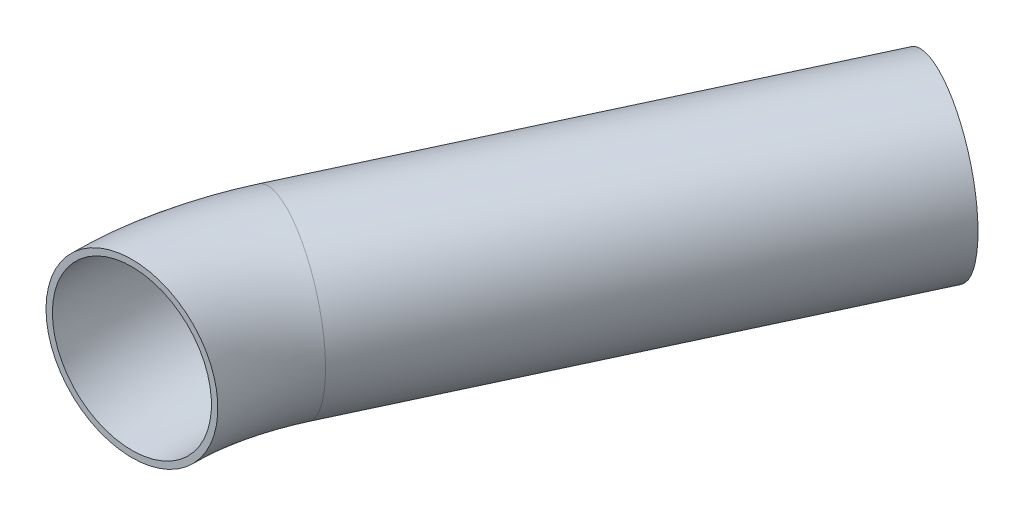
SolidWorks part; units mm, degrees
material "AISI 321 Annealed Stainless Steel (SS)"
ref_plane "Front Plane" through (0, 0, 0) normal (0, 0, 1) x (1, 0, 0)
ref_plane "Top Plane" through (0, 0, 0) normal (0, 1, 0) x (1, 0, 0)
ref_plane "Right Plane" through (0, 0, 0) normal (1, 0, 0) x (0, 0, -1)
sketch "Sketch1" plane through (0, 0, 0) normal (0, 1, 0) x (1, 0, 0)
  line L0 (0, 0) -> (0, -78.2018) construction
  line L1 (7.1393, 32.2035) -> (47.0481, 117.788) construction
  line L2 (7.1393, 32.2035) -> (60.8119, 147.3046)
  arc A0 (0, 0) -> (7.1393, 32.2035) centre (76.2, 0) cw
  dimension "D2" = 76.2
  dimension "D1" = 155
  dimension "D3" = 127
sketch "Sketch2" plane through (0, 0, 0) normal (0, 0, 1) x (1, 0, 0)
  circle A0 centre (0, 0) radius 22.225
  circle A1 centre (0, 0) radius 20.574
  dimension "D1" = 44.45
  dimension "D2" = 1.651
sweep "Sweep1" add profiles "Sketch2" path "Sketch1"
